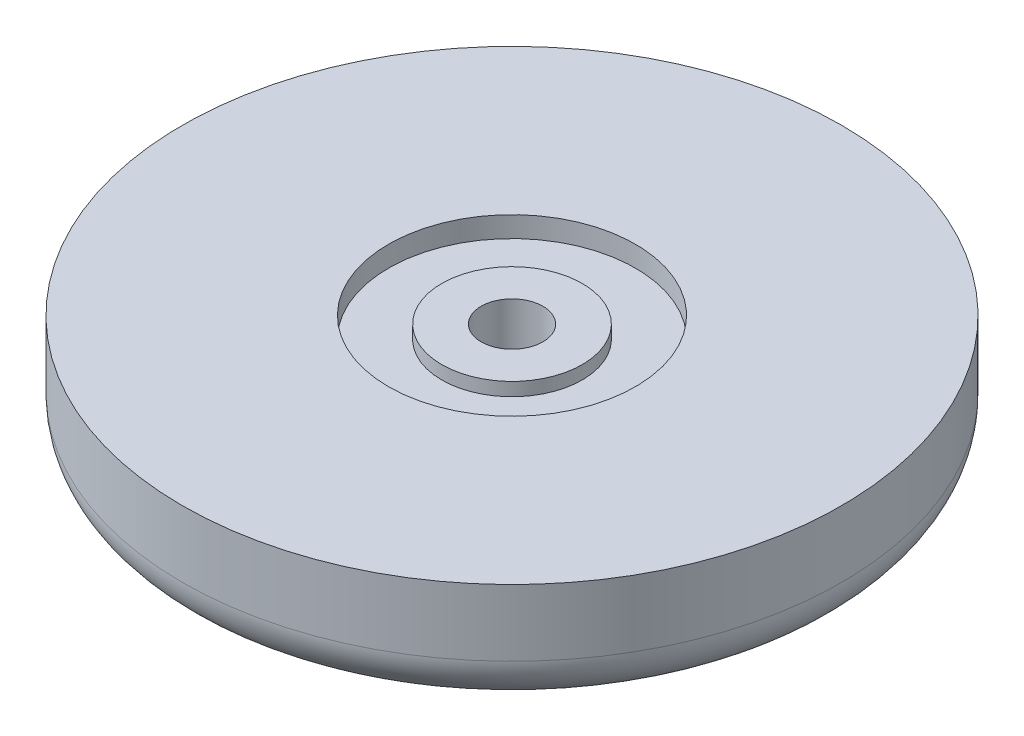
SolidWorks part; units mm, degrees
ref_plane "Front Plane" through (0, 0, 0) normal (0, 0, 1) x (1, 0, 0)
ref_plane "Top Plane" through (0, 0, 0) normal (0, 1, 0) x (1, 0, 0)
ref_plane "Right Plane" through (0, 0, 0) normal (1, 0, 0) x (0, 0, -1)
sketch "Sketch1" plane through (0, 0, 0) normal (0, 1, 0) x (1, 0, 0)
  circle A0 centre (0, 0) radius 44.069
  dimension "D1" = 88.138
extrude "Boss-Extrude1" add sketch "Sketch1" along normal blind 15.24
sketch "Sketch3" plane through (0, 15.24, 0) normal (0, 1, 0) x (1, 0, 0)
  circle A0 centre (0, 0) radius 16.51
  dimension "D1" = 33.02
extrude "Cut-Extrude1" cut sketch "Sketch3" against normal blind 2.7718
sketch "Sketch4" plane through (0, 12.4682, 0) normal (0, 1, 0) x (1, 0, 0)
  circle A0 centre (0, 0) radius 4.1275
  dimension "D1" = 8.255
extrude "Cut-Extrude2" cut sketch "Sketch4" against normal through all
sketch "Sketch5" plane through (0, 12.4682, 0) normal (0, 1, 0) x (1, 0, 0)
  circle A0 centre (0, 0) radius 4.1275 construction
  circle A1 centre (0, 0) radius 4.1275
  circle A2 centre (0, 0) radius 9.398
  dimension "D1" = 18.796
extrude "Boss-Extrude2" add sketch "Sketch5" along normal blind 1.778
fillet "Fillet1" radius 6.35 1 edges at (0, 0, 44.069)
sketch "Sketch6" plane through (0, 0, 0) normal (0, -1, 0) x (1, 0, 0)
  circle A0 centre (0, 0) radius 24.765
  circle A1 centre (0, 0) radius 31.75
  dimension "D1" = 49.53
  dimension "D2" = 63.5
extrude "Cut-Extrude3" cut sketch "Sketch6" against normal blind 1.27
